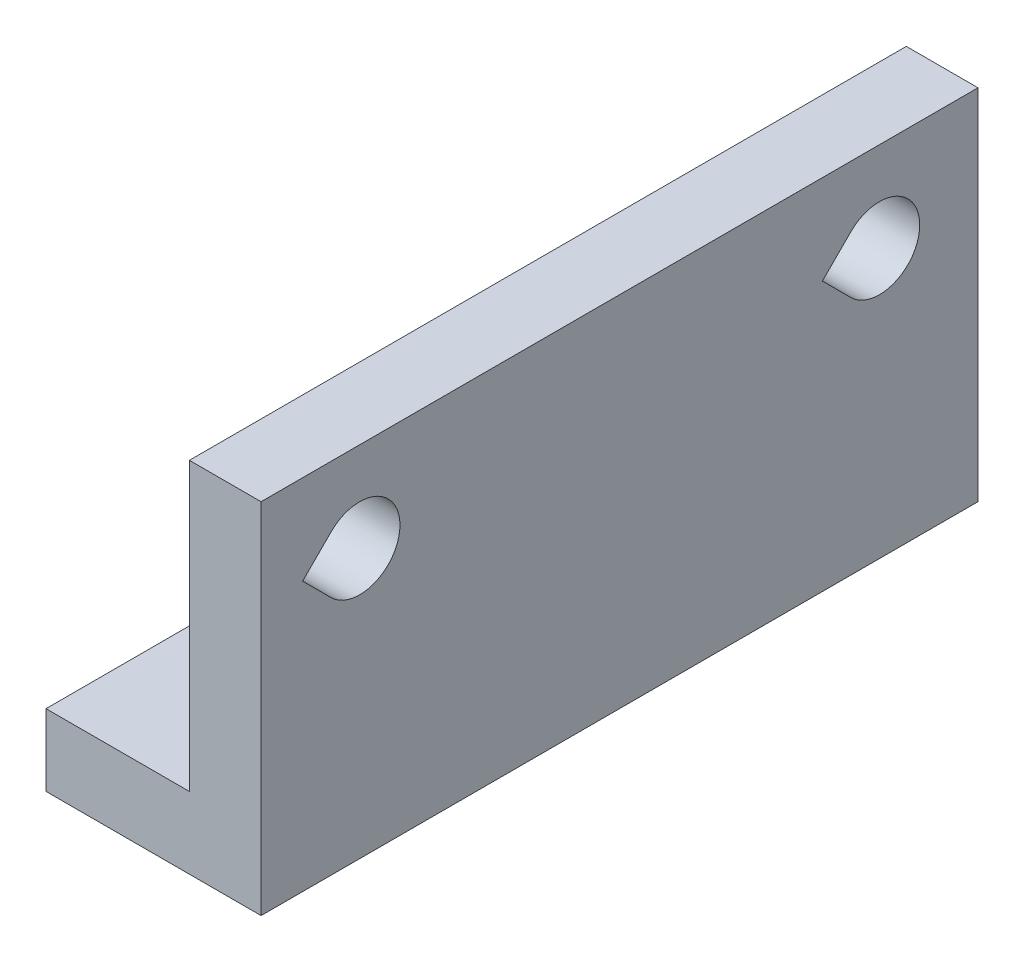
SolidWorks part; units mm, degrees
material "Printed PLA"
ref_plane "Front Plane" through (0, 0, 0) normal (0, 0, 1) x (1, 0, 0)
ref_plane "Top Plane" through (0, 0, 0) normal (0, 1, 0) x (1, 0, 0)
ref_plane "Right Plane" through (0, 0, 0) normal (1, 0, 0) x (0, 0, -1)
sketch "Sketch1" plane through (0, 0, 0) normal (0, 0, 1) x (1, 0, 0)
  line L0 (-15, 0) -> (15, 0)
  line L1 (15, 0) -> (15, 4)
  line L2 (15, 4) -> (7, 4)
  line L3 (7, 4) -> (7, 20)
  line L4 (7, 20) -> (3, 20)
  line L5 (3, 20) -> (3, 4)
  line L6 (3, 4) -> (-3, 4)
  line L7 (-3, 4) -> (-3, 20)
  line L8 (-3, 20) -> (-7, 20)
  line L9 (-7, 20) -> (-7, 4)
  line L10 (-7, 4) -> (-15, 4)
  line L11 (-15, 4) -> (-15, 0)
  dimension "D1" = 30
  dimension "D2" = 4
  dimension "D3" = 6
  dimension "D4" = 4
  dimension "D5" = 20
extrude "Boss-Extrude1" add sketch "Sketch1" along normal blind 40
sketch "Sketch2" plane through (0, 4, 0) normal (0, 1, 0) x (1, 0, 0)
  line L0 (11, -12) -> (-11, -12) construction
  line L1 (0, -12) -> (0, 0) construction
  line L2 (3, 0) -> (-3, 0) construction
  line L3 (-12.591, -13.591) -> (-11, -15.182)
  line L4 (-11, -15.182) -> (-9.409, -13.591)
  line L5 (-11, -15.182) -> (-11, -12) construction
  line L6 (9.409, -13.591) -> (11, -15.182)
  line L7 (11, -15.182) -> (12.591, -13.591)
  line L8 (11, -15.182) -> (11, -12) construction
  arc A0 (-9.409, -13.591) -> (-12.591, -13.591) centre (-11, -12) ccw
  arc A1 (12.591, -13.591) -> (9.409, -13.591) centre (11, -12) ccw
  dimension "D2" = 4.5
  dimension "D1" = 22
  dimension "D3" = 12
extrude "Cut-Extrude1" cut sketch "Sketch2" against normal through all
sketch "Sketch3" plane through (7, 0, 0) normal (1, 0, 0) x (0, 0, -1)
  line L0 (-40, 0) -> (0, 0) construction
  line L2 (-7.091, 16.591) -> (-8.682, 15)
  line L3 (-8.682, 15) -> (-7.091, 13.409)
  line L4 (-8.682, 15) -> (-5.5, 15) construction
  line L5 (0, 4) -> (0, 20) construction
  line L6 (-5.5, 15) -> (-34.5, 15) construction
  line L7 (-36.091, 16.591) -> (-37.682, 15)
  line L8 (-37.682, 15) -> (-36.091, 13.409)
  line L9 (-37.682, 15) -> (-34.5, 15) construction
  arc A0 (-7.091, 13.409) -> (-7.091, 16.591) centre (-5.5, 15) ccw
  arc A1 (-36.091, 13.409) -> (-36.091, 16.591) centre (-34.5, 15) ccw
  dimension "D1" = 4.5
  dimension "D3" = 5.5
  dimension "D2" = 15
  dimension "D5" = 29
  dimension "D4" = 2
extrude "Cut-Extrude2" cut sketch "Sketch3" against normal through all
sketch "Sketch8" plane through (0, 4, 0) normal (0, 1, 0) x (1, 0, 0)
  line L1 (-3, 0) -> (3, 0)
  line L2 (-3, 0) -> (-3, -40)
  line L3 (-3, -40) -> (3, -40)
  line L4 (3, 0) -> (3, -40)
extrude "Cut-Extrude4" cut sketch "Sketch8" against normal through all
delete or keep bodies "Body-Delete1" type delete bodies bodies 111
